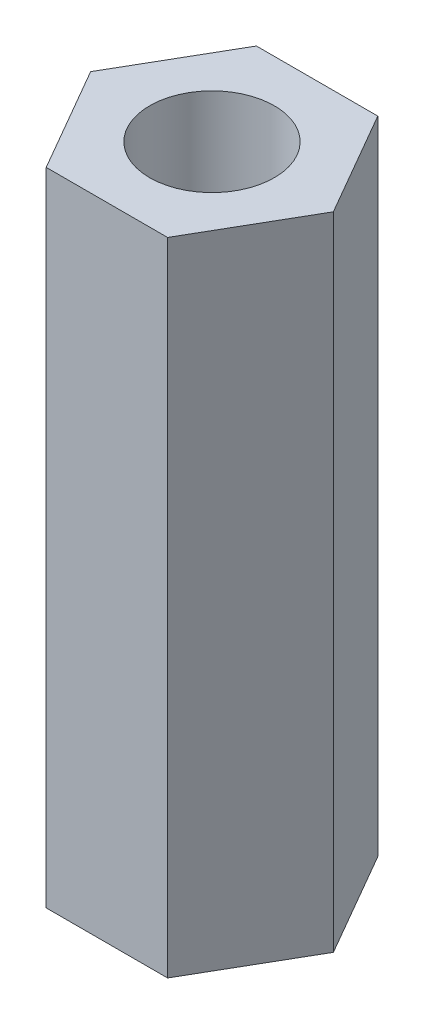
SolidWorks part; units mm, degrees
material "ABS PC"
ref_plane "Front Plane" through (0, 0, 0) normal (0, 0, 1) x (1, 0, 0)
ref_plane "Top Plane" through (0, 0, 0) normal (0, 1, 0) x (1, 0, 0)
ref_plane "Right Plane" through (0, 0, 0) normal (1, 0, 0) x (0, 0, -1)
sketch "Sketch1" plane through (0, 0, 0) normal (0, 1, 0) x (1, 0, 0)
  line L1 (3.4064, 0) -> (1.7032, 2.95)
  line L2 (1.7032, 2.95) -> (-1.7032, 2.95)
  line L3 (-1.7032, 2.95) -> (-3.4064, 0)
  line L4 (-3.4064, 0) -> (-1.7032, -2.95)
  line L5 (-1.7032, -2.95) -> (1.7032, -2.95)
  line L6 (1.7032, -2.95) -> (3.4064, 0)
  circle A0 centre (0, 0) radius 1.75
  circle A1 centre (0, 0) radius 2.95 construction
  point P3 (0, 0)
  dimension "D1" = 3.5
  dimension "D2" = 5.9
extrude "Boss-Extrude1" add sketch "Sketch1" along normal mid plane 18
